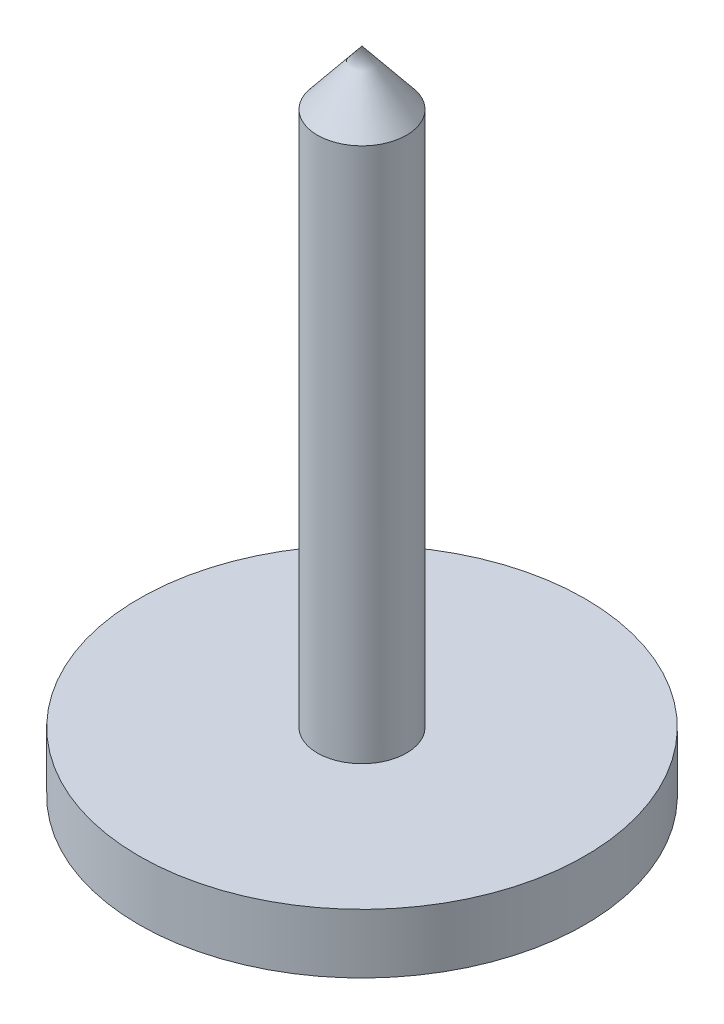
SolidWorks part; units mm, degrees
ref_plane "Front Plane" through (0, 0, 0) normal (0, 0, 1) x (1, 0, 0)
ref_plane "Top Plane" through (0, 0, 0) normal (0, 1, 0) x (1, 0, 0)
ref_plane "Right Plane" through (0, 0, 0) normal (1, 0, 0) x (0, 0, -1)
sketch "Sketch1" plane through (0, 0, 0) normal (0, 0, 1) x (1, 0, 0)
  line L0 (0, -21.4489) -> (0, 109.2396) construction
  line L1 (0, 0) -> (37.5, 0)
  line L2 (37.5, 0) -> (37.5, 10)
  line L3 (37.5, 10) -> (7.5, 10)
  line L4 (7.5, 10) -> (7.5, 100)
  line L5 (7.5, 100) -> (0, 109.2396)
  line L6 (0, 109.2396) -> (0, 0)
  point P6 (0, 109.2396)
  dimension "D1" = 37.5
  dimension "D2" = 10
  dimension "D3" = 90
  dimension "D4" = 7.5
revolve "Revolve1" add sketch "Sketch1" angle 360 about L6
